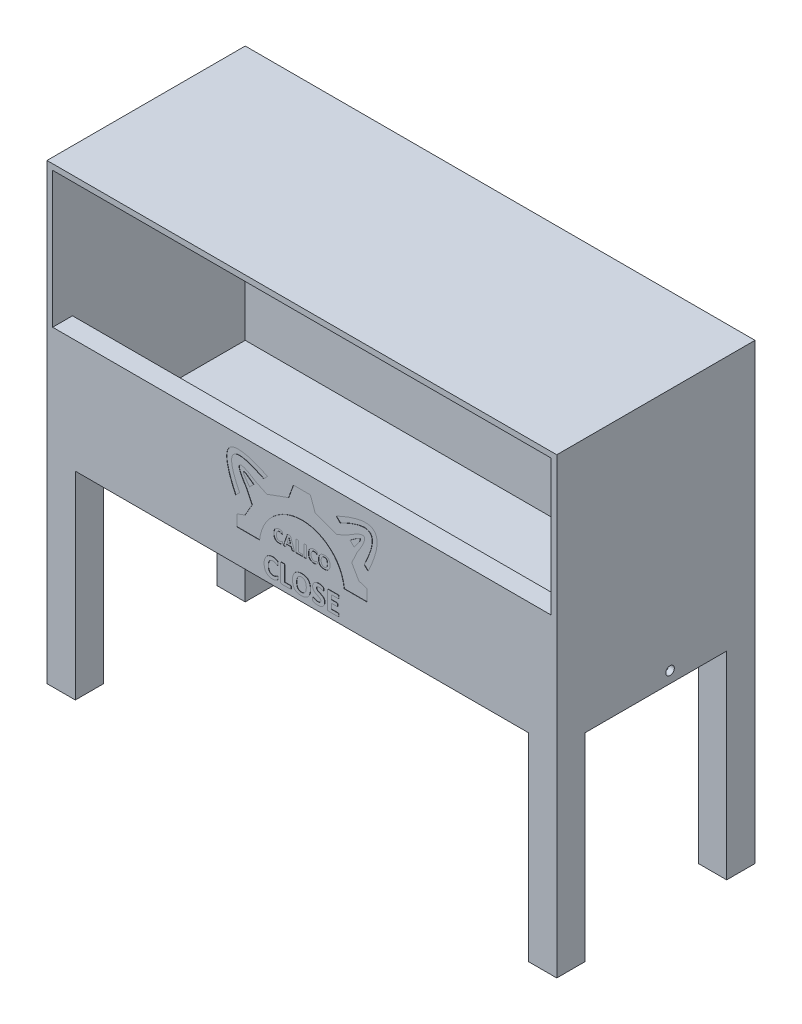
SolidWorks part; units mm, degrees
other "Markup1"
sketch "Sketch8" plane through (900, 450, 500) normal (0.4782, 0.6709, 0.5667) x (0.8556, -0.2105, -0.4728)
sketch "Sketch9" plane through (900, 450, 500) normal (0.4782, 0.6709, 0.5667) x (0.8556, -0.2105, -0.4728)
sketch "Sketch10" plane through (900, 450, 700) normal (0.4782, 0.6709, 0.5667) x (0.8556, -0.2105, -0.4728)
sketch "Sketch12" plane through (900, 450, 700) normal (0.4782, 0.6709, 0.5667) x (0.8556, -0.2105, -0.4728)
ref_plane "Front Plane" through (0, 0, 0) normal (0, 0, 1) x (1, 0, 0)
ref_plane "Top Plane" through (0, 0, 0) normal (0, 1, 0) x (1, 0, 0)
ref_plane "Right Plane" through (0, 0, 0) normal (1, 0, 0) x (0, 0, -1)
sketch "Sketch2" plane through (0, 0, 0) normal (0, 0, 1) x (1, 0, 0)
  line L1 (-900, 450) -> (900, 450)
  line L2 (-900, 450) -> (-900, -450)
  line L3 (-900, -450) -> (900, -450)
  line L4 (900, 450) -> (900, -450)
  line L5 (-900, 450) -> (900, -450) construction
  line L6 (-900, -450) -> (900, 450) construction
  point P0 (0, 0)
  dimension "D1" = 1800
  dimension "D2" = 900
extrude "Boss-Extrude1" add sketch "Sketch2" along normal blind 700
shell "Shell1" thickness 20
sketch "Sketch4" plane through (0, 0, 700) normal (0, 0, 1) x (1, 0, 0)
  line L0 (900, -450) -> (900, 450) construction
  line L1 (-900, -450) -> (900, -450)
  line L2 (-900, -450) -> (-900, -50)
  line L3 (-900, -50) -> (900, -50)
  line L4 (900, -450) -> (900, -50)
  dimension "D1" = 400
extrude "Boss-Extrude2" add sketch "Sketch4" against normal blind 20
sketch "Sketch5" plane through (0, 0, 680) normal (0, 0, -1) x (-1, 0, 0)
  line L0 (880, -430) -> (880, -50) construction
  line L1 (-880, -50) -> (880, -50)
  line L2 (-880, -50) -> (-880, -70)
  line L3 (-880, -70) -> (880, -70)
  line L4 (880, -50) -> (880, -70)
  dimension "D1" = 20
extrude "Boss-Extrude3" add sketch "Sketch5" along normal blind 50
sketch "Sketch6" plane through (0, -450, 0) normal (0, -1, 0) x (1, 0, 0)
  line L0 (0, 0) -> (0, 700) construction
  line L1 (-900, 700) -> (-800, 700)
  line L2 (-900, 700) -> (-900, 600)
  line L3 (-900, 600) -> (-800, 600)
  line L4 (-800, 700) -> (-800, 600)
  line L5 (-900, 0) -> (-800, 0)
  line L6 (-900, 0) -> (-900, 100)
  line L7 (-900, 100) -> (-800, 100)
  line L8 (-800, 0) -> (-800, 100)
  line L9 (-900, 0) -> (900, 0) construction
  line L10 (-900, 700) -> (900, 700) construction
  line L11 (800, 0) -> (800, 100)
  line L12 (900, 0) -> (800, 0)
  line L13 (900, 0) -> (900, 100)
  line L14 (900, 100) -> (800, 100)
  line L15 (900, 600) -> (800, 600)
  line L16 (900, 700) -> (900, 600)
  line L17 (900, 700) -> (800, 700)
  line L18 (800, 700) -> (800, 600)
  dimension "D1" = 100
  dimension "D2" = 100
  dimension "D3" = 100
  dimension "D4" = 100
extrude "Boss-Extrude4" add sketch "Sketch6" along normal blind 700
sketch "Sketch11" plane through (900, 0, 0) normal (1, 0, 0) x (0, 0, -1)
  line L0 (-600, -450) -> (-100, -450) construction
  line L1 (-700, -1150) -> (-700, 450) construction
  circle A0 centre (-300, -410) radius 15
  dimension "D1" = 30
  dimension "D2" = 40
  dimension "D3" = 400
extrude "Cut-Extrude3" cut sketch "Sketch11" against normal up to next
sketch "Sketch15" plane through (0, 0, 700) normal (0, 0, 1) x (1, 0, 0)
  line L0 (-800, -450) -> (800, -450) construction
  line L1 (-229.2677, -335.1959) -> (-149.2677, -335.1959)
  line L2 (0, -350) -> (0, -315.1959) construction
  line L4 (-229.2677, -335.1959) -> (-229.2677, -295.1959)
  line L5 (-229.2677, -295.1959) -> (-201.0769, -284.9353)
  line L6 (-201.0769, -284.9353) -> (-176.0769, -241.634)
  line L7 (-176.0769, -241.634) -> (-195.0947, -200.8502)
  line L8 (-184.4881, -190.2436) -> (-170.346, -176.1015)
  line L9 (-159.7394, -165.4949) -> (-123.4871, -182.3996)
  line L10 (-123.4871, -182.3996) -> (-47.101, -154.5973)
  line L11 (-47.101, -154.5973) -> (-30, -107.6127)
  line L12 (-30, -107.6127) -> (30, -107.6127)
  line L13 (47.101, -154.5973) -> (30, -107.6127)
  line L14 (123.4871, -182.3996) -> (47.101, -154.5973)
  line L15 (159.7394, -165.4949) -> (123.4871, -182.3996)
  line L16 (184.4881, -190.2436) -> (170.346, -176.1015)
  line L17 (176.0769, -241.634) -> (195.0947, -200.8502)
  line L18 (201.0769, -284.9353) -> (176.0769, -241.634)
  line L19 (229.2677, -295.1959) -> (201.0769, -284.9353)
  line L20 (229.2677, -335.1959) -> (229.2677, -295.1959)
  line L21 (177.417, -183.1725) -> (219.8435, -140.7461) construction
  line L22 (219.8435, -140.7461) -> (241.0567, -119.5329) construction
  line L23 (233.9856, -239.7411) -> (195.0947, -200.8502) construction
  line L24 (120.8485, -126.604) -> (134.9906, -140.7461)
  line L25 (219.8435, -225.5989) -> (233.9856, -239.7411)
  line L26 (-219.8435, -225.5989) -> (-233.9856, -239.7411)
  line L27 (-120.8485, -126.604) -> (-134.9906, -140.7461)
  line L28 (149.2677, -335.1959) -> (229.2677, -335.1959)
  line L29 (0, -315.1959) -> (0, 0) construction
  line L30 (159.7394, -165.4949) -> (120.8485, -126.604) construction
  line L31 (184.4881, -190.2436) -> (170.346, -176.1015) construction
  line L32 (241.0567, -119.5329) -> (255.1988, -105.3908) construction
  arc A1 (-149.2677, -335.1959) -> (149.2677, -335.1959) centre (0, -350) cw
  spline S0 degree 2 poles (159.7394, -165.4949) (262.2699, -98.3197) (195.0947, -200.8502) knots 0 0 0 1 1 1
  spline S1 degree 2 poles (170.346, -176.1015) (233.9856, -126.604) (184.4881, -190.2436) knots 0 0 0 1 1 1
  spline S2 degree 2 poles (-170.346, -176.1015) (-233.9856, -126.604) (-184.4881, -190.2436) knots 0 0 0 1 1 1
  spline S3 degree 2 poles (-159.7394, -165.4949) (-262.2699, -98.3197) (-195.0947, -200.8502) knots 0 0 0 1 1 1
  spline S4 degree 2 poles (120.8485, -126.604) (332.9805, -27.609) (233.9856, -239.7411) knots 0 0 0 1 1 1
  spline S5 degree 2 poles (134.9906, -140.7461) (304.6963, -55.8933) (219.8435, -225.5989) knots 0 0 0 1 1 1
  spline S6 degree 2 poles (-120.8485, -126.604) (-332.9805, -27.609) (-233.9856, -239.7411) knots 0 0 0 1 1 1
  spline S7 degree 2 poles (-134.9906, -140.7461) (-304.6963, -55.8933) (-219.8435, -225.5989) knots 0 0 0 1 1 1
  spline S8 degree 2 poles (-159.7394, -165.4949) (-262.2699, -98.3197) (-195.0947, -200.8502) knots 0 0 0 1 1 1
  spline S9 degree 2 poles (-170.346, -176.1015) (-233.9856, -126.604) (-184.4881, -190.2436) knots 0 0 0 1 1 1
  point P25 (0, -107.6127)
  point P47 (127.9196, -133.6751)
  point P51 (-127.9196, -133.6751)
  dimension "D3" = 150
  dimension "D29" = 20
  dimension "D2" = 100
  dimension "D4" = 15
  dimension "D5" = 80
  dimension "D6" = 149.2677
  dimension "D7" = 40
  dimension "D8" = 110
  dimension "D9" = 140
  dimension "D10" = 50
  dimension "D11" = 235
  dimension "D12" = 30
  dimension "D13" = 45
  dimension "D14" = 50
  dimension "D15" = 110
  dimension "D16" = 110
  dimension "D17" = 40
  dimension "D18" = 135
  dimension "D19" = 130
  dimension "D20" = 50
  dimension "D21" = 30
  dimension "D22" = 15
  dimension "D23" = 60
  dimension "D24" = 20
  dimension "D25" = 160
  dimension "D26" = 30
  dimension "D27" = 20
  dimension "D28" = 20
  dimension "D30" = 35
extrude "Cut-Extrude7" cut sketch "Sketch15" against normal blind 1 contours L9 S3 L7 L6 L5 L4 L1 A1 L28 L20 L19 L18 L17 S0 L15 L14 L13 L12 L11 L10 L16 S1 S2 L8 | S7 L27 S6 L26 | L24 S5 L25 S4
sketch "Sketch16" plane through (0, 0, 700) normal (0, 0, 1) x (1, 0, 0)
  line L0 (-144.6224, -310.1959) -> (144.6224, -310.1959) construction
  line L1 (-229.2677, -335.1959) -> (-149.2677, -335.1959) construction
  arc A0 (149.2677, -335.1959) -> (-149.2677, -335.1959) centre (0, -350) ccw construction
  text T0 "CALICO" font "Calibri" height in points 160
  dimension "D1" = 25
extrude "Cut-Extrude8" cut sketch "Sketch16" against normal blind 1
sketch "Sketch17" plane through (0, 0, 700) normal (0, 0, 1) x (1, 0, 0)
  line L0 (-900, -430) -> (900, -430) construction
  line L1 (-900, 450) -> (-900, -1150) construction
  line L2 (900, -1150) -> (900, 450) construction
  line L3 (-800, -450) -> (800, -450) construction
  text T0 "CLOSE" font "Calibri" height in points 250
  dimension "D1" = 20
extrude "Boss-Extrude5" add sketch "Sketch17" along normal blind 1
equation "\"D3@Sketch6\"=\"D1@Sketch6\""
equation "\"D4@Sketch6\"=\"D2@Sketch6\""
equation "\"D2@Sketch6\"=\"D1@Sketch6\""
